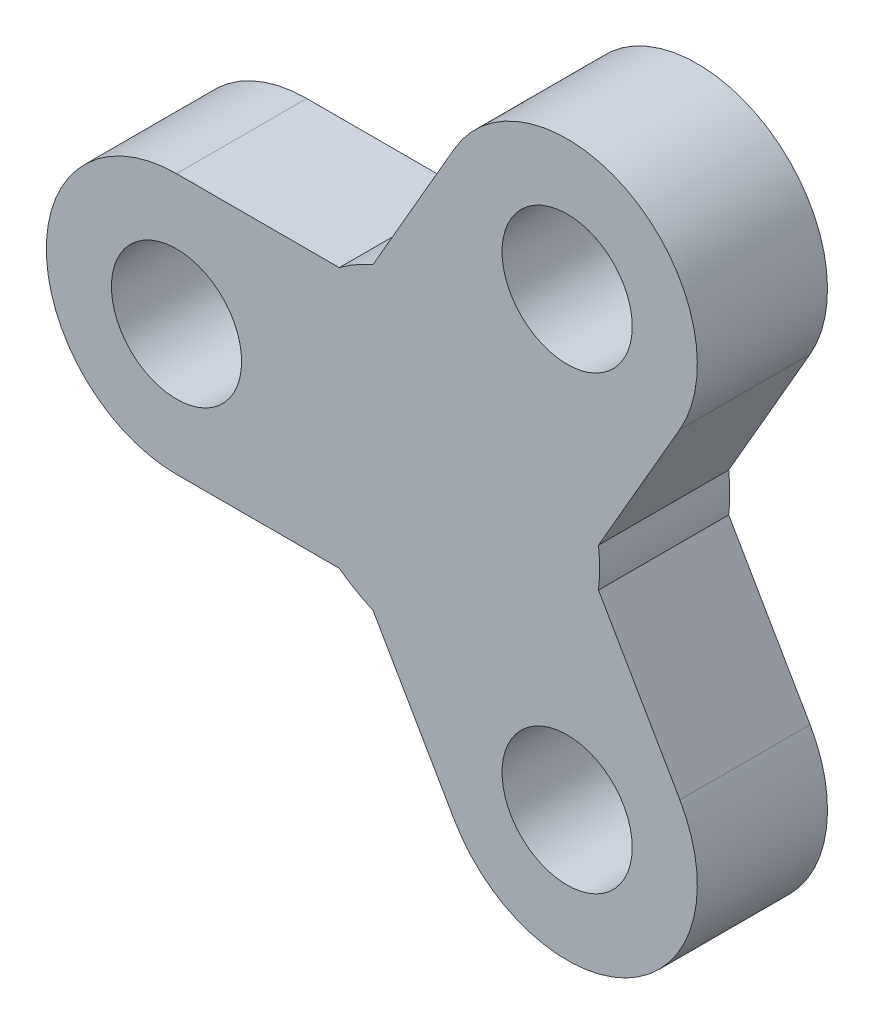
SolidWorks part; units mm, degrees
ref_plane "Alzado" through (0, 0, 0) normal (0, 0, 1) x (1, 0, 0)
ref_plane "Planta" through (0, 0, 0) normal (0, 1, 0) x (1, 0, 0)
ref_plane "Vista lateral" through (0, 0, 0) normal (1, 0, 0) x (0, 0, -1)
sketch "Croquis1" plane through (0, 0, 0) normal (0, 0, 1) x (1, 0, 0)
  line L0 (-20, 10) -> (-7.5, 10)
  line L1 (-20, -10) -> (-7.5, -10)
  line L2 (1.3397, 22.3205) -> (-4.9103, 11.4952)
  line L3 (18.6603, 12.3205) -> (12.4103, 1.4952)
  line L4 (18.6603, -12.3205) -> (12.4103, -1.4952)
  line L5 (1.3397, -22.3205) -> (-4.9103, -11.4952)
  circle A0 centre (0, 0) radius 12.5 construction
  circle A1 centre (0, 0) radius 20 construction
  circle A2 centre (-20, 0) radius 5
  arc A3 (-20, 10) -> (-20, -10) centre (-20, 0) ccw
  arc A4 (18.6603, 12.3205) -> (1.3397, 22.3205) centre (10, 17.3205) ccw
  circle A5 centre (10, 17.3205) radius 5
  arc A6 (1.3397, -22.3205) -> (18.6603, -12.3205) centre (10, -17.3205) ccw
  circle A7 centre (10, -17.3205) radius 5
  arc A8 (-7.5, 10) -> (-4.9103, 11.4952) centre (0, 0) cw
  arc A9 (12.4103, 1.4952) -> (12.4103, -1.4952) centre (0, 0) cw
  arc A10 (-7.5, -10) -> (-4.9103, -11.4952) centre (0, 0) ccw
  point P25 (0, 0)
  dimension "D1" = 25
  dimension "D2" = 40
  dimension "D3" = 10
  dimension "D4" = 10
  dimension "D5" = 3
extrude "Saliente-Extruir1" add sketch "Croquis1" along normal blind 10
